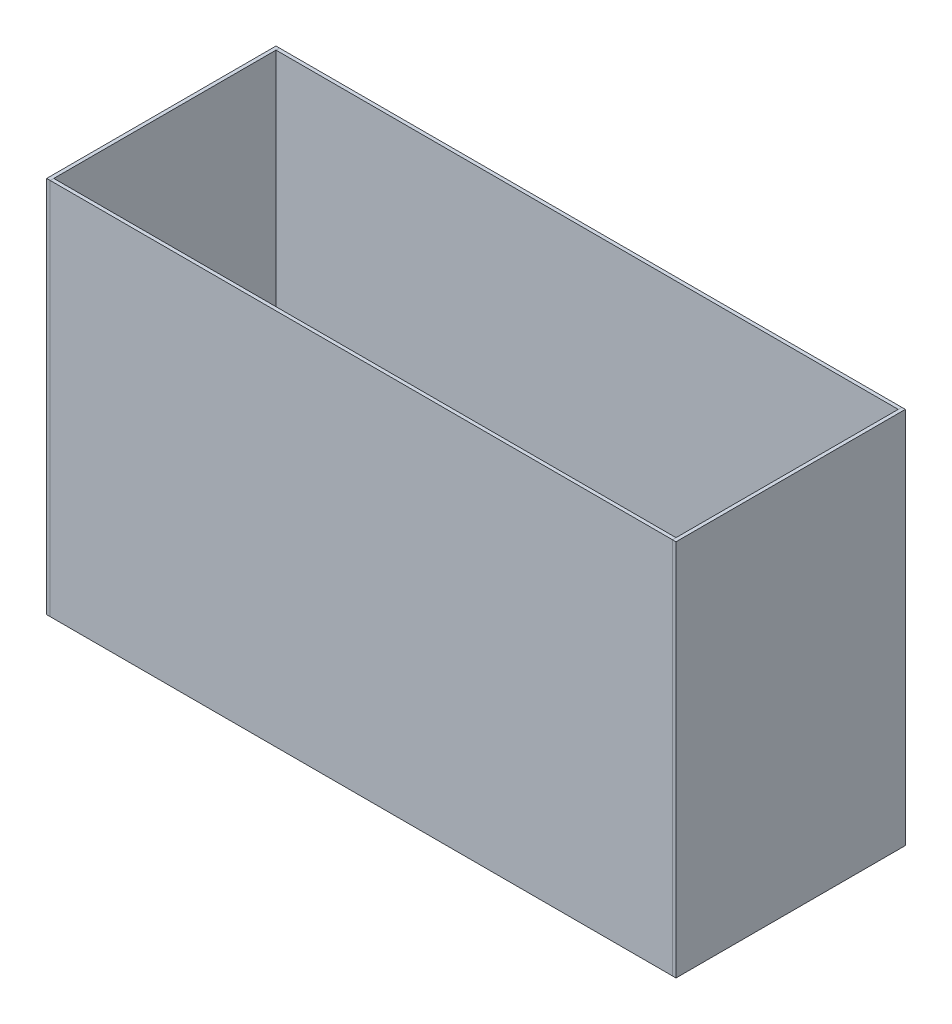
SolidWorks part; units mm, degrees
ref_plane "前视基准面" through (0, 0, 0) normal (0, 0, 1) x (1, 0, 0)
ref_plane "上视基准面" through (0, 0, 0) normal (0, 1, 0) x (1, 0, 0)
ref_plane "右视基准面" through (0, 0, 0) normal (1, 0, 0) x (0, 0, -1)
other "Configuration Table"
sketch "草图1" plane through (0, 0, 0) normal (0, 0, 1) x (1, 0, 0)
  line L0 (0, 0) -> (1400, 0)
  line L1 (1400, 0) -> (1400, 850)
  line L2 (1400, 850) -> (0, 850)
  line L3 (0, 850) -> (0, 0)
extrude "PC_observation_wall_left_t8" add sketch "草图1" along normal blind 8 from offset 8 separate body
sketch "草图2" plane through (0, 0, 0) normal (0, 0, 1) x (1, 0, 0)
  line L0 (0, 0) -> (1400, 0)
  line L1 (1400, 0) -> (1400, 850)
  line L2 (1400, 850) -> (0, 850)
  line L3 (0, 850) -> (0, 0)
extrude "PC_observation_wall_right_t8" add sketch "草图2" along normal blind 8 from offset 500 separate body
sketch "草图3" plane through (0, 0, 0) normal (0, 0, 1) x (1, 0, 0)
  line L0 (-8, 0) -> (0, 0)
  line L1 (0, 0) -> (0, 850)
  line L2 (0, 850) -> (-8, 850)
  line L3 (-8, 850) -> (-8, 0)
extrude "PC_rear_end_t8" add sketch "草图3" along normal blind 516 from offset 8 separate body
sketch "草图4" plane through (0, 0, 0) normal (0, 0, 1) x (1, 0, 0)
  line L0 (1400, 0) -> (1408, 0)
  line L1 (1408, 0) -> (1408, 850)
  line L2 (1408, 850) -> (1400, 850)
  line L3 (1400, 850) -> (1400, 0)
extrude "PC_toe_end_t8" add sketch "草图4" along normal blind 516 from offset 8 separate body
